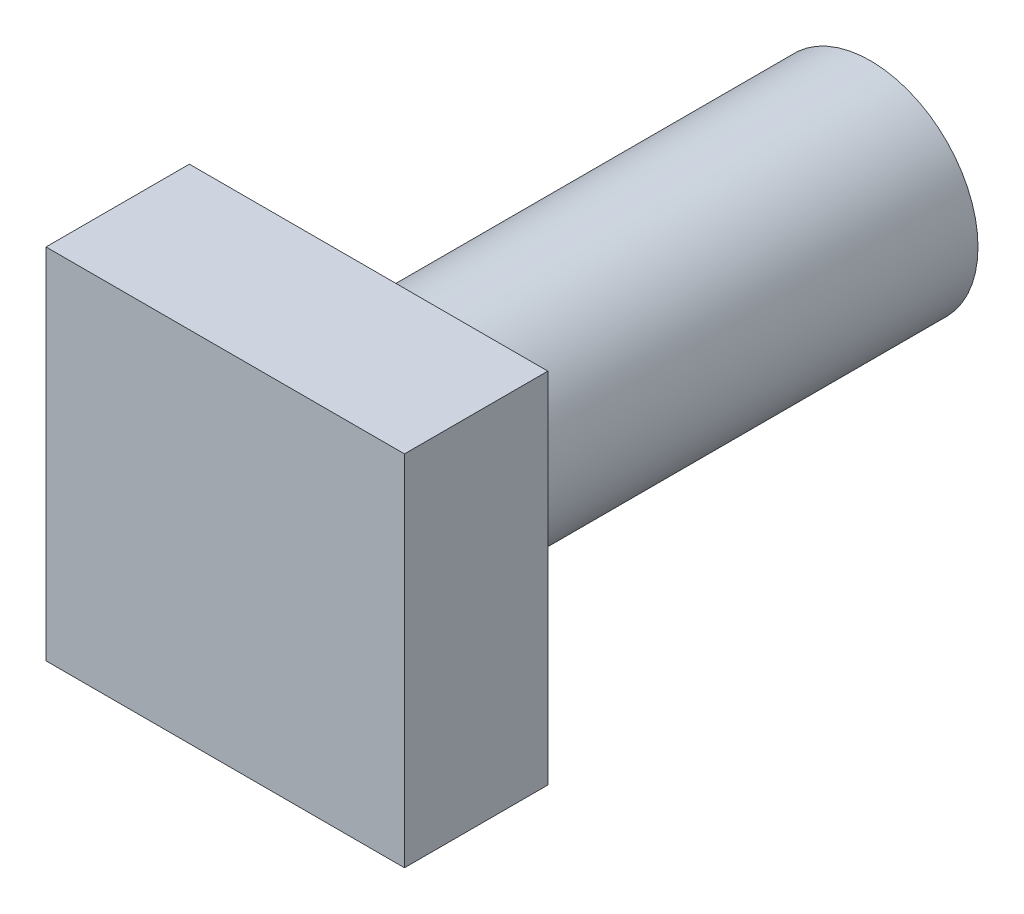
SolidWorks part; units mm, degrees
ref_plane "Front Plane" through (0, 0, 0) normal (0, 0, 1) x (1, 0, 0)
ref_plane "Top Plane" through (0, 0, 0) normal (0, 1, 0) x (1, 0, 0)
ref_plane "Right Plane" through (0, 0, 0) normal (1, 0, 0) x (0, 0, -1)
sketch "Sketch1" plane through (0, 0, 0) normal (0, 0, 1) x (1, 0, 0)
  circle A0 centre (0, 0) radius 1.905
  dimension "D1" = 3.81
extrude "Boss-Extrude1" add sketch "Sketch1" against normal blind 8.89
sketch "Sketch2" plane through (0, 0, 0) normal (0, 0, 1) x (1, 0, 0)
  line L1 (-3.175, -3.175) -> (3.175, -3.175)
  line L2 (-3.175, -3.175) -> (-3.175, 3.175)
  line L3 (-3.175, 3.175) -> (3.175, 3.175)
  line L4 (3.175, -3.175) -> (3.175, 3.175)
  line L5 (-3.175, -3.175) -> (3.175, 3.175) construction
  line L6 (-3.175, 3.175) -> (3.175, -3.175) construction
  point P0 (0, 0)
  dimension "D1" = 6.35
  dimension "D2" = 6.35
extrude "Boss-Extrude2" add sketch "Sketch2" along normal blind 2.54
equation "\"OD\"= 0.15 - 0.00035'Shaft OD [in]"
equation "\"Length\"= 0.35'Shaft Length [in]"
equation "\"D1@Boss-Extrude1\"=\"Length\""
